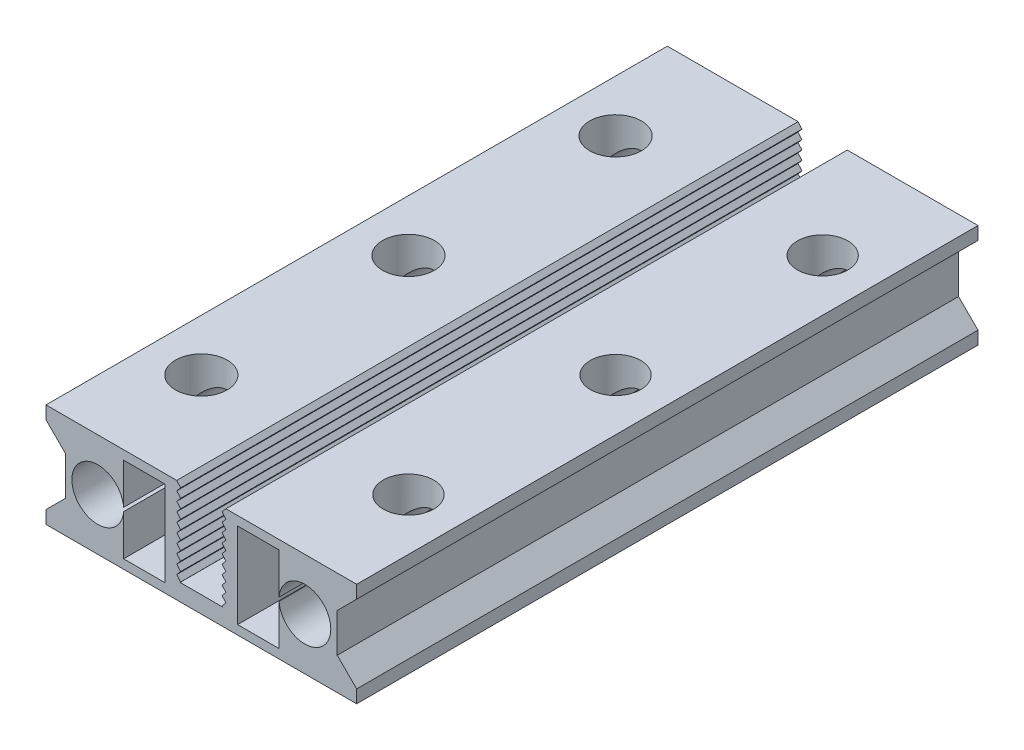
SolidWorks part; units mm, degrees
ref_plane "前视基准面" through (0, 0, 0) normal (0, 0, 1) x (1, 0, 0)
ref_plane "上视基准面" through (0, 0, 0) normal (0, 1, 0) x (1, 0, 0)
ref_plane "右视基准面" through (0, 0, 0) normal (1, 0, 0) x (0, 0, -1)
sketch "草图1" plane through (0, 0, 0) normal (0, 0, 1) x (1, 0, 0)
  line L0 (-12, 8) -> (-12, 7)
  line L1 (-12, 7) -> (-10.5, 5.5)
  line L2 (-10.5, 5.5) -> (-10.5, 2.5)
  line L3 (-10.5, 2.5) -> (-12, 1)
  line L4 (-12, 1) -> (-12, 0)
  line L5 (-12, 0) -> (12, 0)
  line L6 (12, 0) -> (12, 1)
  line L7 (12, 1) -> (10.5, 2.5)
  line L8 (10.5, 2.5) -> (10.5, 5.5)
  line L9 (10.5, 5.5) -> (12, 7)
  line L10 (12, 7) -> (12, 8)
  line L11 (12, 8) -> (1.9, 8)
  line L12 (0, 0) -> (0, 8) construction
  line L13 (-8, 4) -> (8, 4) construction
  line L14 (-1.9, 8) -> (-1.9, 1.3)
  line L15 (-6.005, 7.3) -> (-2.8, 7.3)
  line L16 (-6.005, 7.3) -> (-6.005, 4.1413)
  line L17 (-6.005, 0.7) -> (-2.8, 0.7)
  line L18 (-2.8, 7.3) -> (-2.8, 0.7)
  line L19 (-1.9, 1.3) -> (1.9, 1.3)
  line L20 (1.9, 1.3) -> (1.9, 8)
  line L21 (-1.9, 8) -> (-12, 8)
  line L22 (-6.005, 3.8587) -> (-6.005, 0.7)
  line L23 (2.8, 7.3) -> (6.005, 7.3)
  line L24 (2.8, 7.3) -> (2.8, 0.7)
  line L25 (2.8, 0.7) -> (6.005, 0.7)
  line L26 (6.005, 7.3) -> (6.005, 4.1413)
  line L27 (6.005, 3.8587) -> (6.005, 0.7)
  arc A0 (-6.005, 4.1413) -> (-6, 4) centre (-8, 4) ccw
  arc A1 (6.005, 3.8587) -> (6.005, 4.1413) centre (8, 4) ccw
  point P19 (10.5, 4)
  point P24 (-2.8, 4)
  point P27 (0, 1.3)
  dimension "D4" = 4
  dimension "D1" = 24
  dimension "D2" = 8
  dimension "D3" = 45
  dimension "D5" = 16
  dimension "D6" = 8
  dimension "D7" = 3
  dimension "D8" = 1
  dimension "D9" = 4
  dimension "D10" = 3.8
  dimension "D11" = 1.3
  dimension "D12" = 5.6
  dimension "D13" = 2.8
  dimension "D14" = 12.01
  dimension "D15" = 0.7
extrude "凸台-拉伸2" add sketch "草图1" along normal blind 48 contours L14 L21 L0 L1 L2 L3 L4 L5 L6 L7 L8 L9 L10 L11 L20 L19 A1 L27 L25 L24 L23 L26 A0 L16 L15 L18 L17 L22
sketch "草图3" plane through (0, 0, 48) normal (0, 0, 1) x (1, 0, 0)
  line L0 (-1.9, 8) -> (-1.6, 7.65)
  line L1 (-1.6, 7.65) -> (-1.9, 7.3)
  line L2 (-1.9, 8) -> (-1.9, 1.3) construction
  line L3 (-1.9, 7.3) -> (-1.9, 8)
  point P7 (-1.9, 7.65)
  dimension "D1" = 0.7
  dimension "D2" = 0.3
extrude "凸台-拉伸3" add sketch "草图3" against normal up to surface (48 mm away) up to face at (5.6025, 4, 0)
pattern_linear "阵列(线性)1" count 10 spacing 0.7 along (0, -1, 0) of "凸台-拉伸3"
mirror "镜向1" about plane through (0, 0, 0) normal (1, 0, 0) of "阵列(线性)1", "凸台-拉伸3"
sketch "草图4" plane through (0, 8, 0) normal (0, 1, 0) x (1, 0, 0)
  line L1 (12, 0) -> (1.9, 0) construction
  circle A0 centre (-8, -8) radius 2
  circle A1 centre (8, -8) radius 1.95
  dimension "D1" = 16
  dimension "D4" = 3.9
  dimension "D5" = 4
  dimension "D2" = 8
  dimension "D3" = 8
extrude "切除-拉伸1" cut sketch "草图4" against normal through all
pattern_linear "阵列(线性)2" count 3 spacing 16 along (0, 0, 1) of "切除-拉伸1"
equation "\"D13@草图1\"=\"D12@草图1\"/2"
